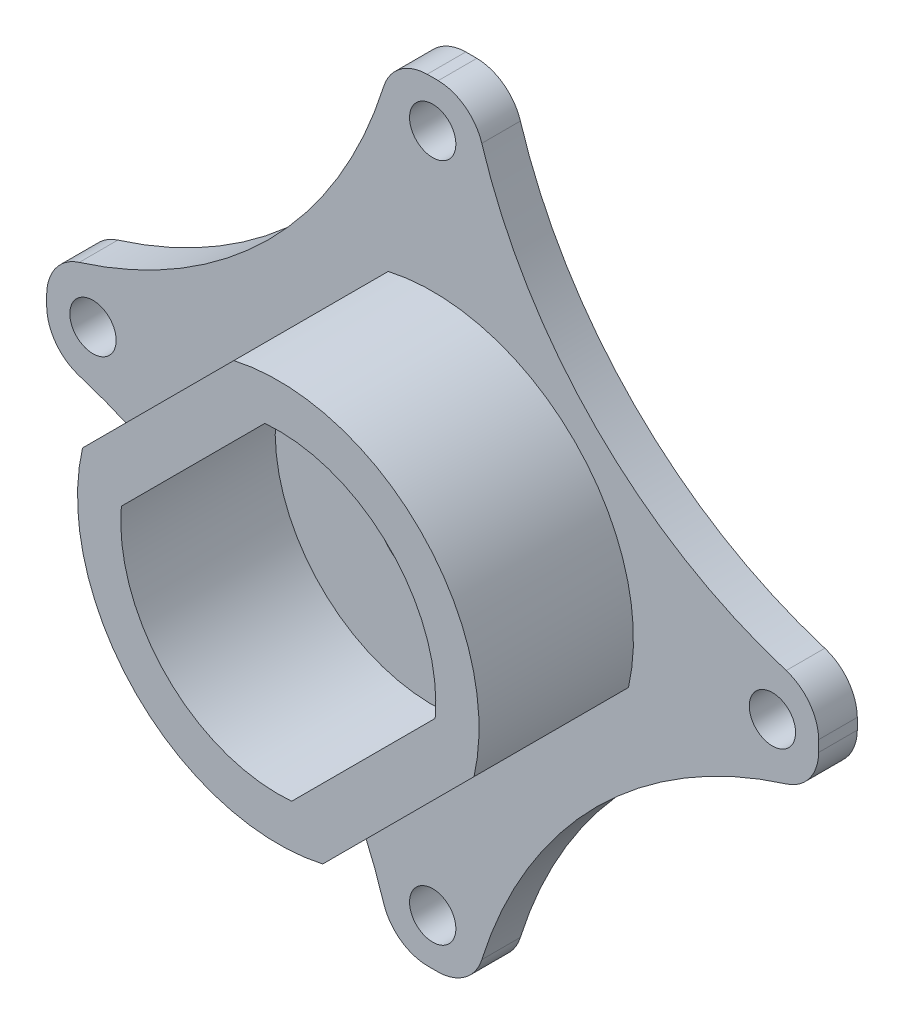
SolidWorks part; units mm, degrees
ref_plane "前视基准面" through (0, 0, 0) normal (0, 0, 1) x (1, 0, 0)
ref_plane "上视基准面" through (0, 0, 0) normal (0, 1, 0) x (1, 0, 0)
ref_plane "右视基准面" through (0, 0, 0) normal (1, 0, 0) x (0, 0, -1)
other "Configuration Table"
sketch "草图1" plane through (0, 0, 0) normal (0, 0, 1) x (1, 0, 0)
  line L0 (0, 0) -> (0, 22) construction
  line L1 (0, 0) -> (22, 0) construction
  circle A0 centre (0, 0) radius 22 construction
  circle A1 centre (0, 0) radius 16.5 construction
  circle A2 centre (0, 0) radius 25
  circle A3 centre (0, 22) radius 1.5
  circle A4 centre (22, 0) radius 1.5
  circle A5 centre (0, -22) radius 1.5
  circle A6 centre (-22, 0) radius 1.5
  dimension "D1" = 44
  dimension "D2" = 33
  dimension "D3" = 3
  dimension "D4" = 3
  dimension "D6" = 90
  dimension "D5" = 3
extrude "凸台-拉伸1" add sketch "草图1" along normal blind 2.5
sketch "草图3" plane through (0, 0, 0) normal (0, 0, -1) x (-1, 0, 0)
  line L0 (0, 0) -> (0, 22) construction
  circle A0 centre (0, 0) radius 10.5
  circle A1 centre (0, 0) radius 4
  circle A2 centre (0, 6.2) radius 1
  circle A3 centre (0, -6.2) radius 1
  dimension "D1" = 21
  dimension "D2" = 8
  dimension "D3" = 2
  dimension "D4" = 2
  dimension "D5" = 6.2
  dimension "D6" = 6.2
extrude "切除-拉伸2" cut sketch "草图3" against normal through all both and the other way through all contours A1
sketch "草图5" plane through (0, 0, 0) normal (0, 0, -1) x (-1, 0, 0)
  line L0 (-31.8198, 31.8198) -> (0, 0) construction
  line L1 (-22, 0) -> (0, 0) construction
  arc A0 (-24.8604, 2.6382) -> (-2.6382, 24.8604) centre (-31.8198, 31.8198) ccw
  circle A5 centre (0, 0) radius 25 construction
  arc A6 (2.6382, 24.8604) -> (24.8604, 2.6382) centre (31.8198, 31.8198) ccw
  circle A7 centre (0, 0) radius 25
  circle A8 centre (0, 0) radius 25
  arc A9 (24.8604, -2.6382) -> (2.6382, -24.8604) centre (31.8198, -31.8198) ccw
  arc A10 (-2.6382, -24.8604) -> (-24.8604, -2.6382) centre (-31.8198, -31.8198) ccw
  point P22 (0, 0)
  circle M3 centre (0, 0) radius 25
  dimension "D2" = 30
  dimension "D1" = 0
  dimension "D4" = 45
  dimension "D5" = 4
  dimension "D3" = 45
extrude "切除-拉伸5" cut sketch "草图5" against normal blind 10 contours A0 M3 | A8 A10 | A8 A9 | A6 M3
fillet "圆角2" radius 3 8 edges at (24.8604, 2.6382, 1.25) (2.6382, 24.8604, 1.25) (-2.6382, 24.8604, 1.25) (-24.8604, 2.6382, 1.25) (-24.8604, -2.6382, 1.25) (-2.6382, -24.8604, 1.25) (2.6382, -24.8604, 1.25) (24.8604, -2.6382, 1.25)
sketch "草图6" plane through (0, 0, 2.5) normal (0, 0, 1) x (1, 0, 0)
  line L0 (-10.163, 0.8679) -> (-0.8679, 10.163)
  line L1 (0, 0) -> (5.4954, 5.4954) construction
  line L2 (0.8679, -10.163) -> (10.163, -0.8679)
  line L3 (-12.6772, 2.8792) -> (-2.8792, 12.6772)
  line L4 (2.8792, -12.6772) -> (12.6772, -2.8792)
  line L5 (0, 0) -> (0, -2.6659) construction
  arc A0 (10.163, -0.8679) -> (-0.8679, 10.163) centre (0, 0) ccw
  arc A1 (-10.163, 0.8679) -> (0.8679, -10.163) centre (0, 0) ccw
  arc A2 (12.6772, -2.8792) -> (-2.8792, 12.6772) centre (0, 0) ccw
  arc A3 (-12.6772, 2.8792) -> (2.8792, -12.6772) centre (0, 0) ccw
  dimension "D1" = 20.4
  dimension "D3" = 26
  dimension "D2" = 15.6
  dimension "D4" = 22
  dimension "D5" = 135
extrude "凸台-拉伸2" add sketch "草图6" along normal blind 10
